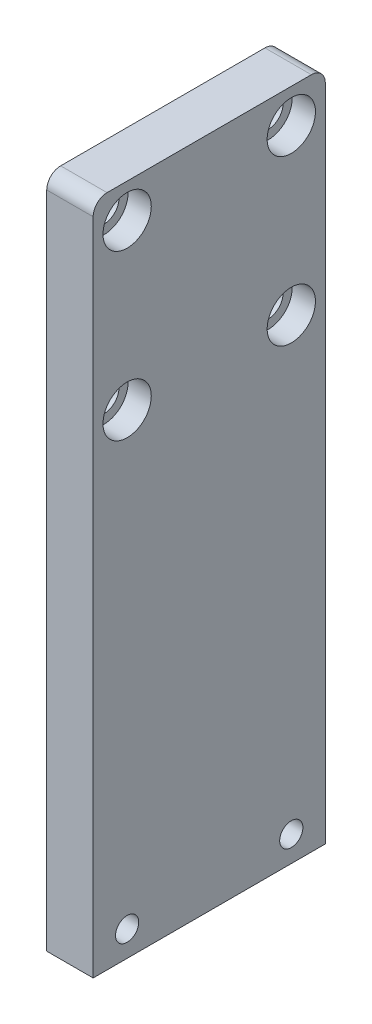
SolidWorks part; units mm, degrees
ref_plane "Alzado" through (0, 0, 0) normal (0, 0, 1) x (1, 0, 0)
ref_plane "Planta" through (0, 0, 0) normal (0, 1, 0) x (1, 0, 0)
ref_plane "Vista lateral" through (0, 0, 0) normal (1, 0, 0) x (0, 0, -1)
sketch "Croquis1" plane through (0, 0, 0) normal (1, 0, 0) x (0, 0, -1)
  line L1 (-25, -120) -> (25, -120)
  line L2 (25, -120) -> (25, 25)
  line L4 (0, 25) -> (0, -120) construction
  line L5 (25, 0) -> (-25, 0) construction
  line L6 (-25, 0) -> (-25, 25)
  line L7 (-25, 0) -> (-25, -120)
  line L8 (-25, 25) -> (0, 25)
  line L9 (0, 25) -> (25, 25)
  line L10 (0, 5.5) -> (0, -5.5) construction
  circle A1 centre (-17.68, 17.68) radius 3.25
  circle A2 centre (17.68, 17.68) radius 3.25
  circle A3 centre (17.68, -17.68) radius 3.25
  circle A4 centre (-17.68, -17.68) radius 3.25
  circle A5 centre (-17.68, -114.5) radius 2.5
  circle A6 centre (17.68, -114.5) radius 2.5
  dimension "D7" = 6.5
  dimension "D11" = 6.5
  dimension "D13" = 5
  dimension "D1" = 25
  dimension "D2" = 25
  dimension "D3" = 17.68
  dimension "D4" = 17.68
  dimension "D5" = 17.68
  dimension "D6" = 120
  dimension "D8" = 17.68
  dimension "D9" = 0
  dimension "D10" = 25
  dimension "D14" = 5.5
  dimension "D15" = 7.32
extrude "Saliente-Extruir1" add sketch "Croquis1" along normal blind 10
sketch "Croquis5" plane through (10, 0, 0) normal (1, 0, 0) x (0, 0, -1)
  circle A0 centre (17.68, 17.68) radius 5.2
  circle A1 centre (-17.68, 17.68) radius 5.2
  circle A2 centre (-17.68, -17.68) radius 5.2
  circle A3 centre (17.68, -17.68) radius 5.2
  dimension "D1" = 10.4
  dimension "D2" = 10.4
  dimension "D3" = 10.4
  dimension "D4" = 10.4
extrude "Cortar-Extruir2" cut sketch "Croquis5" against normal blind 5
fillet "Fillet1" radius 3 2 edges at (5, 25, -25) (5, 25, 25)
sketch "Sketch1" plane through (0, 0, 0) normal (-1, 0, 0) x (0, 0, 1)
  line L0 (0, -5.5) -> (0, 5.5) construction
  circle A0 centre (17.68, -114.5) radius 4.425
  circle A2 centre (-17.68, -114.5) radius 4.425
  dimension "D1" = 8.85
extrude "Cut-Extrude1" cut sketch "Sketch1" against normal blind 5
